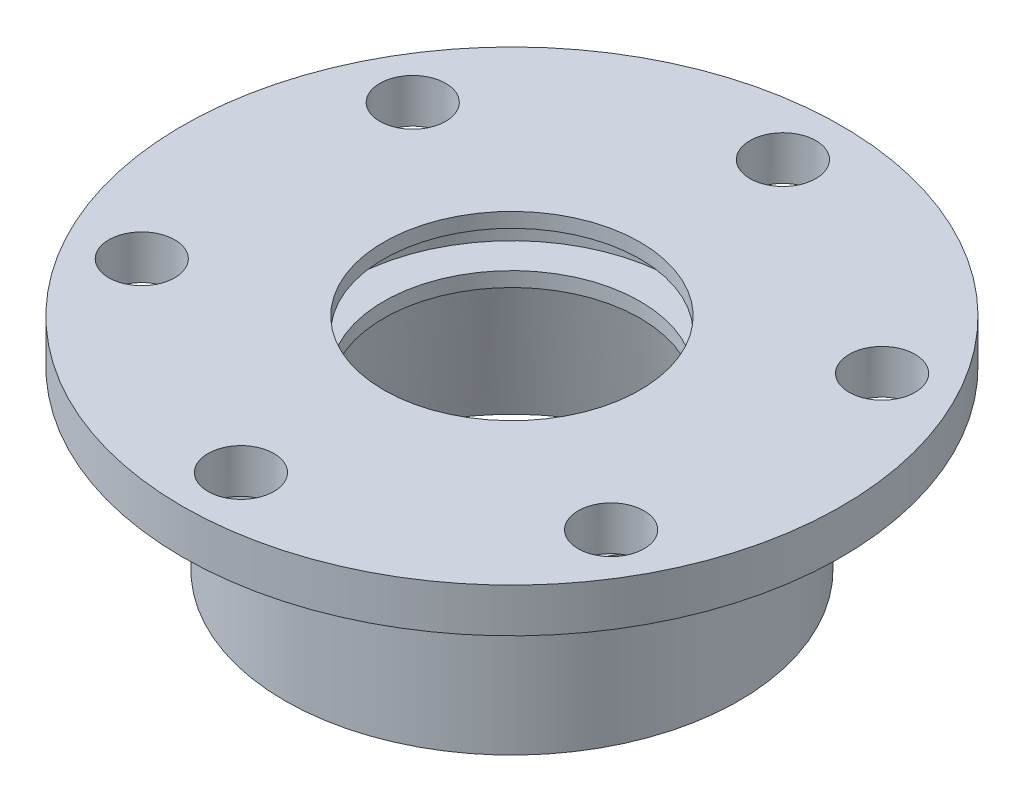
SolidWorks part; units mm, degrees
ref_plane "Front Plane" through (0, 0, 0) normal (0, 0, 1) x (1, 0, 0)
ref_plane "Top Plane" through (0, 0, 0) normal (0, 1, 0) x (1, 0, 0)
ref_plane "Right Plane" through (0, 0, 0) normal (1, 0, 0) x (0, 0, -1)
sketch "Sketch1" plane through (0, 0, 0) normal (0, 0, 1) x (1, 0, 0)
  line L0 (0, 30.6188) -> (0, -35.2308) construction
  line L2 (-45, 30) -> (-45, 24)
  line L3 (-45, 24) -> (-29.5, 24)
  line L4 (-29.5, 24) -> (-29.5, 22.5)
  line L5 (-29.5, 22.5) -> (-31, 22.5)
  line L6 (-31, 22.5) -> (-31, 0)
  line L7 (-31, 0) -> (-26, 0)
  line L8 (-26, 0) -> (-22.2971, 21)
  line L11 (-45, 30) -> (-27, 30)
  line L15 (-27, 30) -> (-17.5, 30)
  line L16 (-17.5, 30) -> (-17.5, 28)
  line L17 (-17.5, 28) -> (-22.5, 28)
  line L18 (-22.5, 28) -> (-22.5, 23)
  line L19 (-22.5, 23) -> (-17.5, 23)
  line L20 (-17.5, 23) -> (-17.5, 21)
  line L21 (-17.5, 21) -> (-22.2971, 21)
  dimension "D1" = 31
  dimension "D2" = 45
  dimension "D3" = 5
  dimension "D4" = 100
  dimension "D5" = 1.5
  dimension "D6" = 15.5
  dimension "D7" = 1.5
  dimension "D8" = 24
  dimension "D9" = 5
  dimension "D10" = 2
  dimension "D11" = 2
  dimension "D12" = 6
  dimension "D13" = 5
  dimension "D14" = 17.5
revolve "Revolve1" add sketch "Sketch1" angle 360 about L0
sketch "Sketch2" plane through (0, 30, 0) normal (0, 1, 0) x (1, 0, 0)
  line L0 (-53.4517, 0) -> (69.7526, 0) construction
  line L1 (0, 51.0634) -> (0, -55.84) construction
  circle A0 centre (0, 37) radius 4.5
  circle A1 centre (32.0429, 18.5) radius 4.5
  circle A2 centre (32.0429, -18.5) radius 4.5
  circle A3 centre (0, -37) radius 4.5
  circle A4 centre (-32.0429, -18.5) radius 4.5
  circle A5 centre (-32.0429, 18.5) radius 4.5
  point P19 (0, 0)
  dimension "D1" = 9
  dimension "D2" = 37
  dimension "D3" = 6
extrude "Cut-Extrude1" cut sketch "Sketch2" against normal up to next
